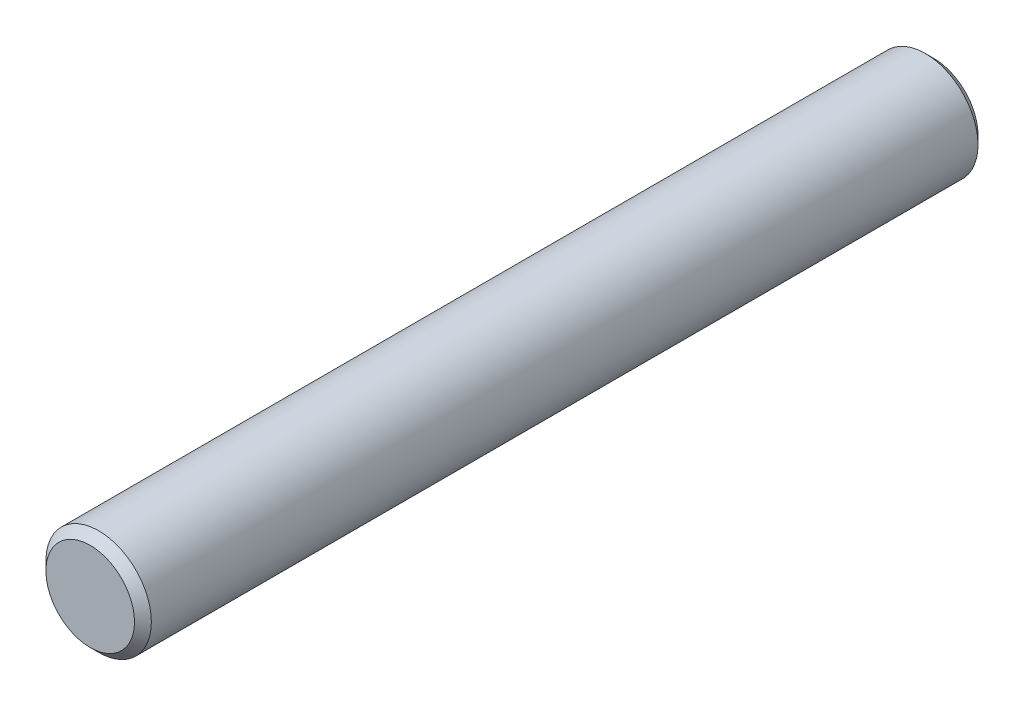
SolidWorks part; units mm, degrees
material "Chrome Stainless Steel"
ref_plane "Front Plane" through (0, 0, 0) normal (0, 0, 1) x (1, 0, 0)
ref_plane "Top Plane" through (0, 0, 0) normal (0, 1, 0) x (1, 0, 0)
ref_plane "Right Plane" through (0, 0, 0) normal (1, 0, 0) x (0, 0, -1)
sketch "Sketch1" plane through (0, 0, 0) normal (0, 0, 1) x (1, 0, 0)
  circle A0 centre (0, 0) radius 1.5875
  dimension "D1" = 3.175
extrude "Boss-Extrude1" add sketch "Sketch1" along normal blind 25.4
chamfer "Chamfer1" distance 0.254 angle 45 2 edges at (1.5875, 0, 25.4) (1.5875, 0, 0)
